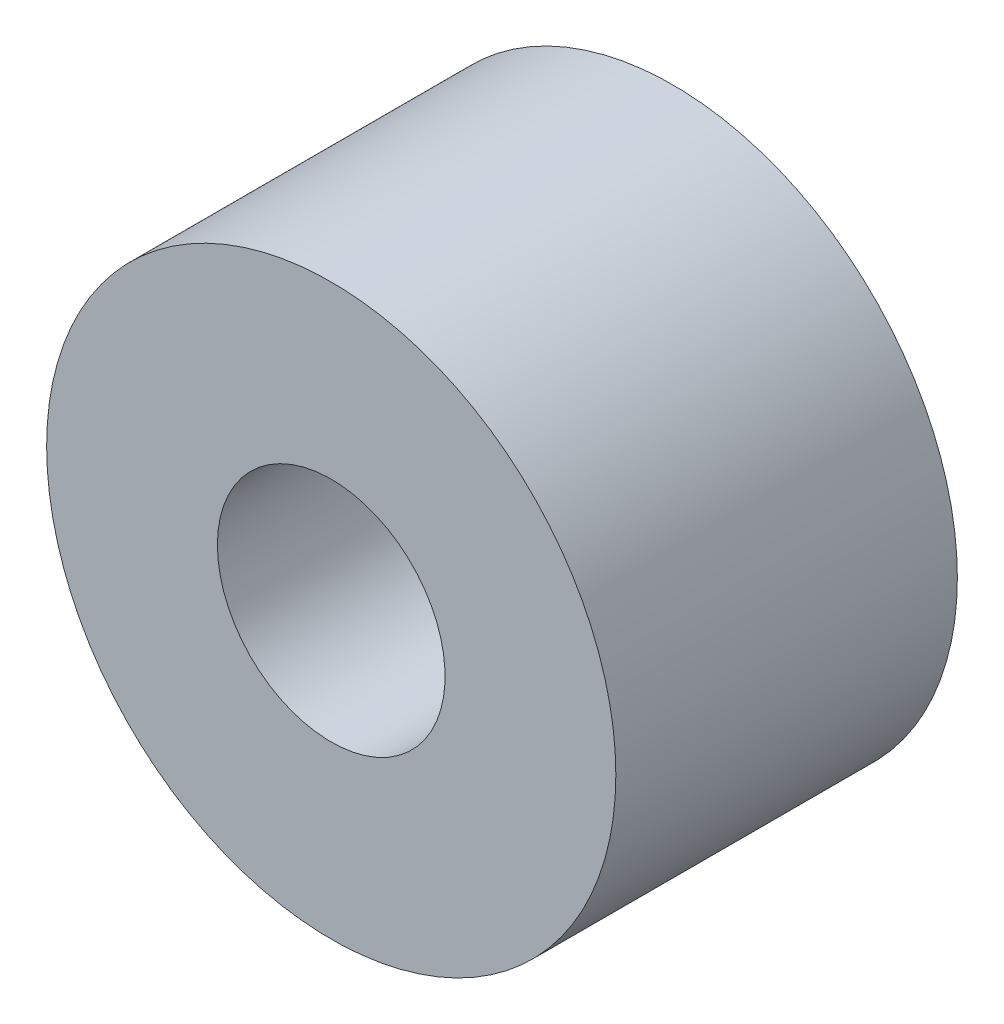
SolidWorks part; units mm, degrees
ref_plane "前视基准面" through (0, 0, 0) normal (0, 0, 1) x (1, 0, 0)
ref_plane "上视基准面" through (0, 0, 0) normal (0, 1, 0) x (1, 0, 0)
ref_plane "右视基准面" through (0, 0, 0) normal (1, 0, 0) x (0, 0, -1)
sketch "草图1" plane through (0, 0, 0) normal (0, 0, 1) x (1, 0, 0)
  circle A0 centre (0, 0) radius 15
  circle A1 centre (0, 0) radius 37.5
extrude "凸台-拉伸1" add sketch "草图1" along normal blind 45
